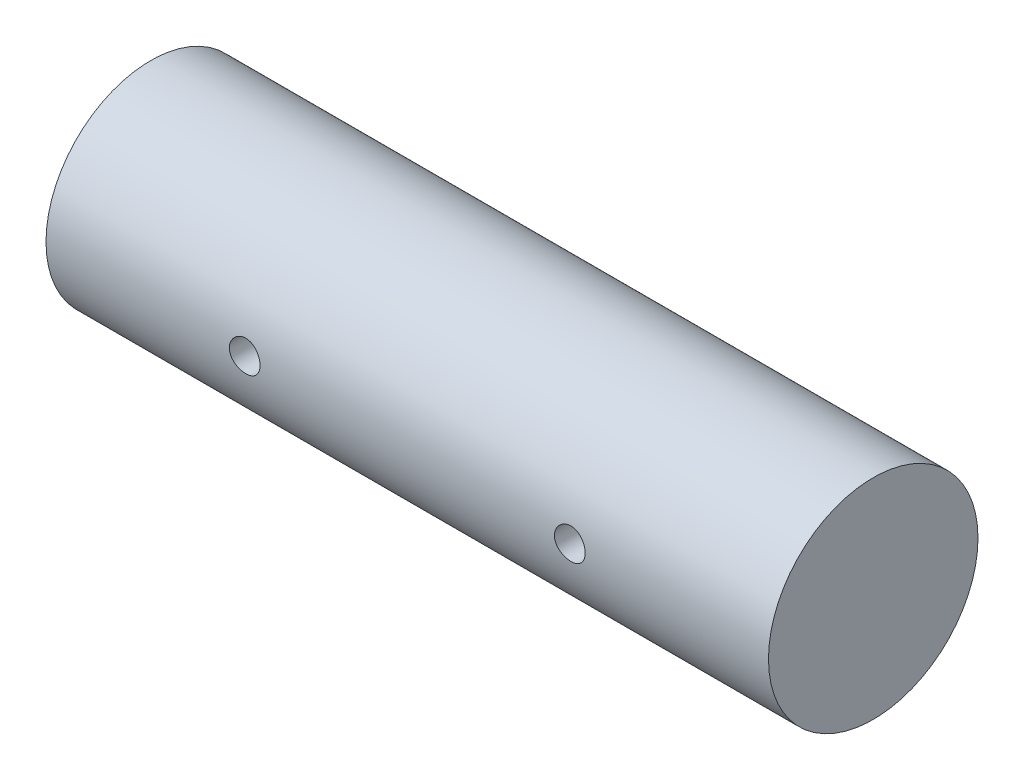
SolidWorks part; units mm, degrees
ref_plane "Front Plane" through (0, 0, 0) normal (0, 0, 1) x (1, 0, 0)
ref_plane "Top Plane" through (0, 0, 0) normal (0, 1, 0) x (1, 0, 0)
ref_plane "Right Plane" through (0, 0, 0) normal (1, 0, 0) x (0, 0, -1)
sketch "Sketch1" plane through (0, 0, 0) normal (1, 0, 0) x (0, 0, -1)
  circle A0 centre (0, 0) radius 11.6
extrude "Boss-Extrude1" add sketch "Sketch1" along normal mid plane 80
sketch "Sketch2" plane through (0, 0, 0) normal (0, 0, 1) x (1, 0, 0)
  circle A0 centre (18, 0) radius 1.7
  circle A1 centre (-18, 0) radius 1.7
extrude "Cut-Extrude1" cut sketch "Sketch2" against normal through all and the other way through all
